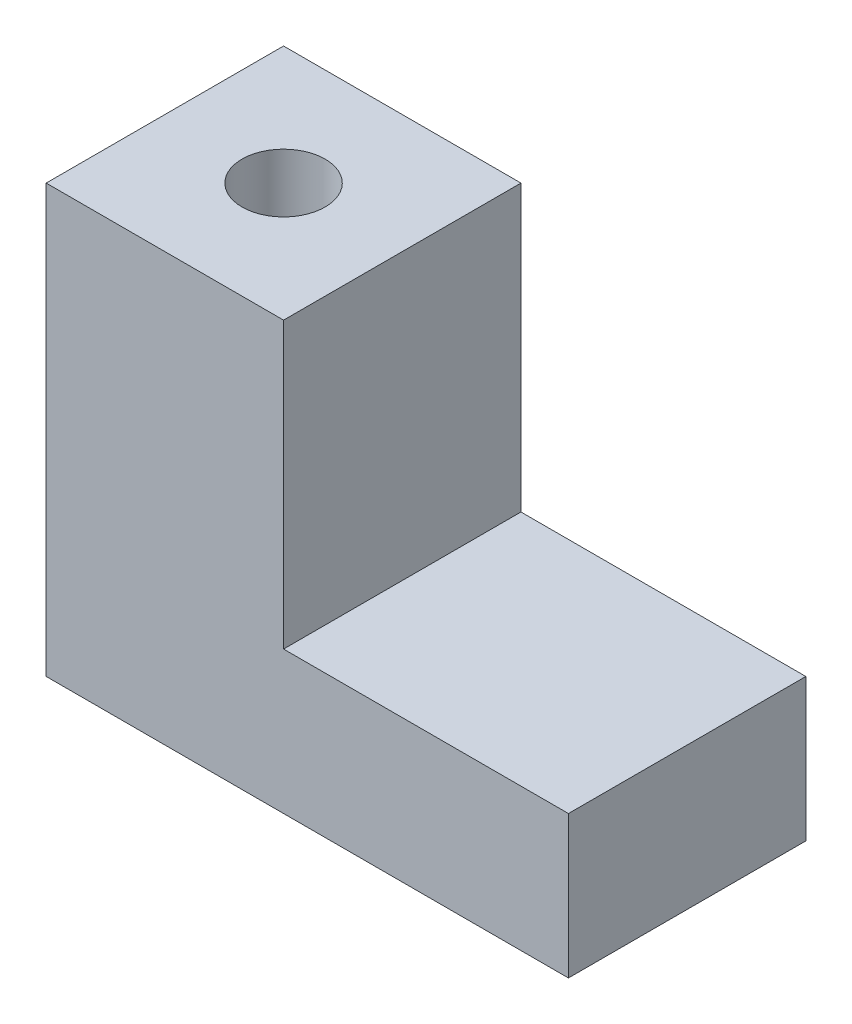
SolidWorks part; units mm, degrees
ref_plane "Front Plane" through (0, 0, 0) normal (0, 0, 1) x (1, 0, 0)
ref_plane "Top Plane" through (0, 0, 0) normal (0, 1, 0) x (1, 0, 0)
ref_plane "Right Plane" through (0, 0, 0) normal (1, 0, 0) x (0, 0, -1)
sketch "Sketch1" plane through (0, 0, 0) normal (0, 1, 0) x (1, 0, 0)
  line L3 (0, 10) -> (22, 10)
  line L4 (22, 10) -> (22, 0)
  line L5 (22, 0) -> (0, 0)
  line L6 (0, 0) -> (0, 10)
  dimension "D3" = 10
extrude "Boss-Extrude1" add sketch "Sketch1" along normal blind 6
sketch "Sketch2" plane through (0, 6, 0) normal (0, 1, 0) x (1, 0, 0)
  line L1 (10, 10) -> (0, 10)
  line L2 (10, 10) -> (10, 0)
  line L3 (10, 0) -> (0, 0)
  line L4 (0, 10) -> (0, 0)
  point P4 (0, 0)
  point P5 (0, 8.946)
extrude "Boss-Extrude2" add sketch "Sketch2" along normal blind 12
sketch "Sketch3" plane through (0, 18, 0) normal (0, 1, 0) x (1, 0, 0)
  line L0 (0, 0) -> (10, 10) construction
  circle A0 centre (5, 5) radius 1.75
  point P6 (0, 0)
  point P7 (0, 0)
  point P8 (0.9227, 0.8374)
  dimension "D1" = 3.5
extrude "Cut-Extrude1" cut sketch "Sketch3" against normal through all
sketch "Sketch4" plane through (0, 0, 0) normal (0, -1, 0) x (1, 0, 0)
  line L0 (5, -5) -> (1.8246, -5) construction
  line L1 (1.8246, -5) -> (3.4123, -7.75)
  line L2 (3.4123, -7.75) -> (6.5877, -7.75)
  line L3 (6.5877, -7.75) -> (8.1754, -5)
  line L4 (8.1754, -5) -> (6.5877, -2.25)
  line L5 (6.5877, -2.25) -> (3.4123, -2.25)
  line L6 (3.4123, -2.25) -> (1.8246, -5)
  circle A0 centre (5, -5) radius 2.75 construction
  dimension "D1" = 5.5
extrude "Cut-Extrude2" cut sketch "Sketch4" against normal blind 3
